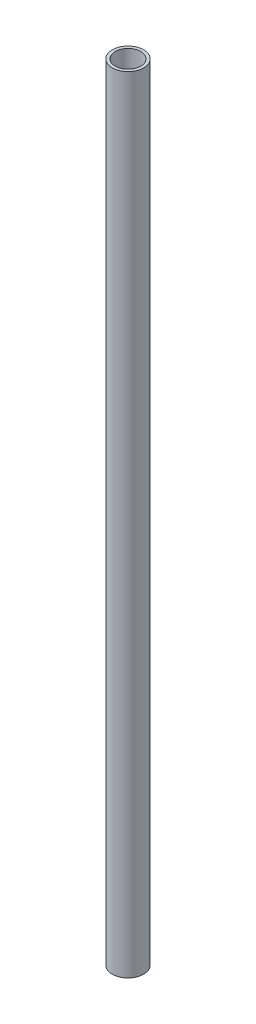
SolidWorks part; units mm, degrees
ref_plane "Front Plane" through (0, 0, 0) normal (0, 0, 1) x (1, 0, 0)
ref_plane "Top Plane" through (0, 0, 0) normal (0, 1, 0) x (1, 0, 0)
ref_plane "Right Plane" through (0, 0, 0) normal (1, 0, 0) x (0, 0, -1)
sketch "Sketch1" plane through (0, 0, 0) normal (0, 1, 0) x (1, 0, 0)
  circle A0 centre (0, 0) radius 6.5
  circle A1 centre (0, 0) radius 8
  dimension "D1" = 13
  dimension "D2" = 16
extrude "Boss-Extrude1" add sketch "Sketch1" along normal blind 400
